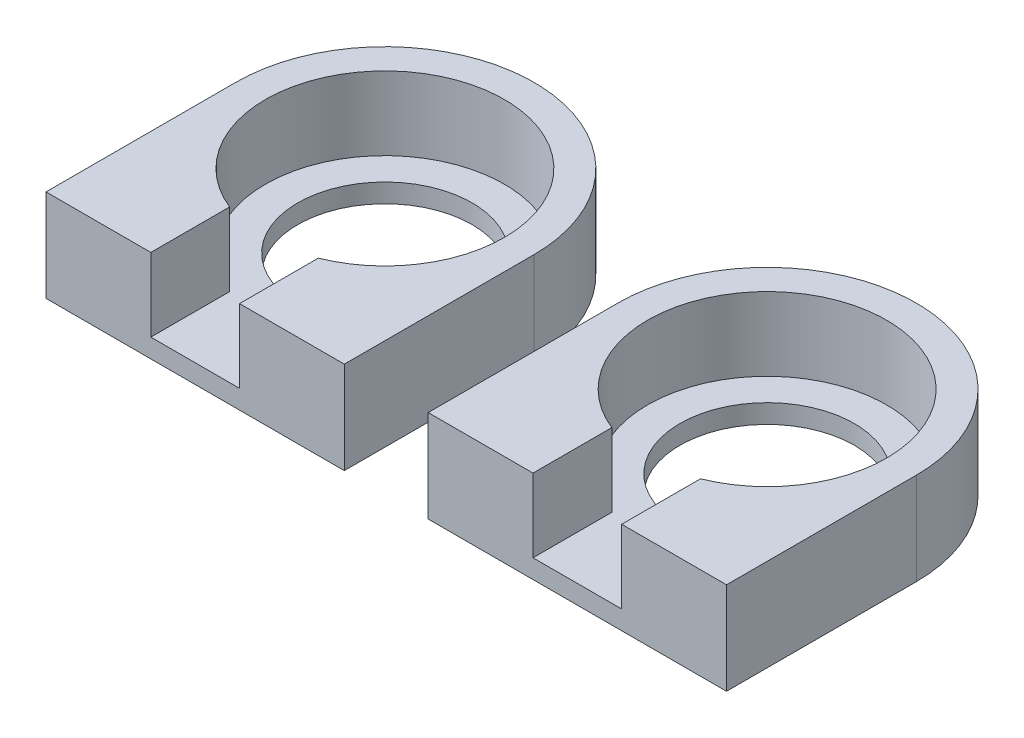
SolidWorks part; units mm, degrees
material "6061-T6 (SS)"
ref_plane "Front Plane" through (0, 0, 0) normal (0, 0, 1) x (1, 0, 0)
ref_plane "Top Plane" through (0, 0, 0) normal (0, 1, 0) x (1, 0, 0)
ref_plane "Right Plane" through (0, 0, 0) normal (1, 0, 0) x (0, 0, -1)
sketch "Sketch1" plane through (0, 0, 0) normal (0, 1, 0) x (1, 0, 0)
  line L0 (-17.7875, -22.6281) -> (17.7875, -22.6281)
  line L31 (-17.7875, 0) -> (-17.7875, -22.6281)
  line L32 (17.7875, 0) -> (17.7875, -22.6281)
  circle A2 centre (0, 0) radius 14.25
  arc A4 (17.7875, 0) -> (-17.7875, 0) centre (0, 0) ccw
  circle A5 centre (0, 0) radius 17.7875 construction
  point P3 (0, -14.2875)
extrude "Boss-Extrude1" add sketch "Sketch1" along normal blind 11
sketch "Sketch3" plane through (0, 11, 0) normal (0, 1, 0) x (1, 0, 0)
  line L17 (17.7875, -22.6281) -> (5.2875, -22.6281) construction
  line L21 (-17.7875, -22.6281) -> (17.7875, -22.6281) construction
  line L23 (-17.7875, -22.6281) -> (-5.2875, -22.6281) construction
  line L25 (-5.2875, -22.6281) -> (5.2875, -22.6281)
  line L26 (5.2875, -22.6281) -> (5.2875, -10.3998)
  line L27 (5.2875, -10.3998) -> (-5.2875, -10.3998)
  line L28 (-5.2875, -10.3998) -> (-5.2875, -22.6281)
sketch "Sketch4" plane through (0, 0, 0) normal (0, -1, 0) x (1, 0, 0)
  circle A0 centre (0, 0) radius 14.25
extrude "Boss-Extrude2" add sketch "Sketch4" against normal blind 2.25
sketch "Sketch5" plane through (0, 2.25, 0) normal (0, 1, 0) x (1, 0, 0)
  circle A0 centre (0, 0) radius 10.4
extrude "Cut-Extrude1" cut sketch "Sketch5" against normal blind 2.25
extrude "Cut-Extrude5" cut sketch "Sketch3" against normal blind 8.75
ref_plane "Plane1" through (22.7875, 0, 0) normal (1, 0, 0) x (0, 0, -1)
sketch "Sketch7" plane through (0, 0, 22.6281) normal (0, 0, 1) x (1, 0, 0)
  line L0 (-17.7875, 0) -> (-17.7875, -1.5)
  line L1 (-17.7875, -1.5) -> (22.7875, -1.5)
  line L2 (22.7875, -10.4839) -> (22.7875, 10.4839) construction
  line L3 (22.7875, -1.5) -> (22.7875, 0)
  line L4 (22.7875, 0) -> (-17.7875, 0)
extrude "Boss-Extrude3" add sketch "Sketch7" against normal blind 45 and the other way blind 5
mirror "Mirror5" about plane through (22.7875, 0, 0) normal (1, 0, 0) of bodies 113
sketch "Sketch8" plane through (0, 0, 27.6281) normal (0, 0, 1) x (1, 0, 0)
  line L8 (63.3625, 0) -> (-17.7875, 0)
  line L9 (-17.7875, 0) -> (-17.7875, -1.5)
  line L10 (-17.7875, -1.5) -> (63.3625, -1.5)
  line L11 (63.3625, -1.5) -> (63.3625, 0)
  line L12 (63.3625, 0) -> (-17.7875, 0)
  line L13 (-17.7875, 0) -> (-17.7875, -1.5)
  line L14 (-17.7875, -1.5) -> (63.3625, -1.5)
  line L15 (63.3625, -1.5) -> (63.3625, 0)
  dimension "D1" = 0
extrude "Cut-Extrude6" cut sketch "Sketch8" against normal blind 60
